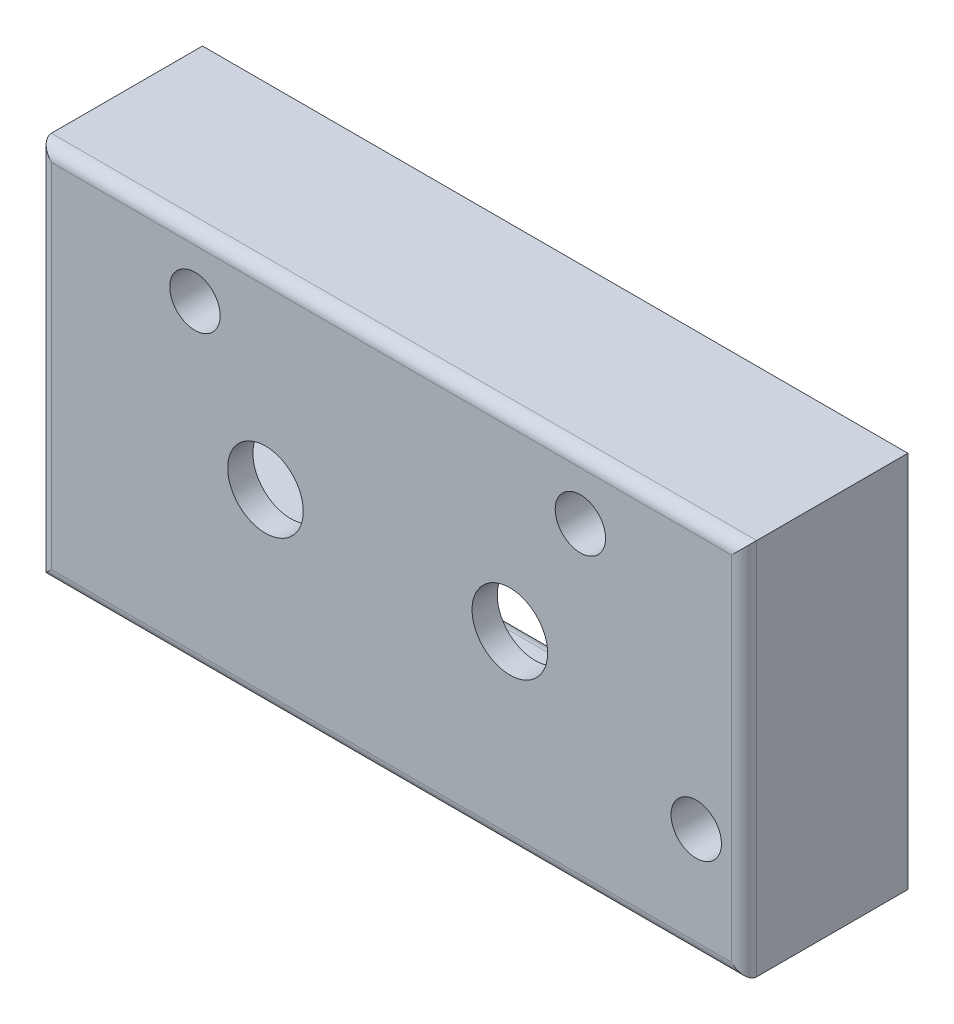
SolidWorks part; units mm, degrees
ref_plane "Plano frontal" through (0, 0, 0) normal (0, 0, 1) x (1, 0, 0)
ref_plane "Plano superior" through (0, 0, 0) normal (0, 1, 0) x (1, 0, 0)
ref_plane "Plano direito" through (0, 0, 0) normal (1, 0, 0) x (0, 0, -1)
sketch "Esboço1" plane through (0, 0, 0) normal (0, 0, 1) x (1, 0, 0)
  line L1 (-14, -7.5) -> (14, -7.5)
  line L2 (-14, -7.5) -> (-14, 7.5)
  line L3 (-14, 7.5) -> (14, 7.5)
  line L4 (14, -7.5) -> (14, 7.5)
  line L5 (-14, -7.5) -> (14, 7.5) construction
  line L6 (-14, 7.5) -> (14, -7.5) construction
  point P0 (0, 0)
  dimension "D1" = 28
  dimension "D2" = 15
extrude "Ressalto-extrusão1" add sketch "Esboço1" along normal blind 6.5
sketch "Esboço2" plane through (0, 0, 0) normal (0, 0, -1) x (-1, 0, 0)
  line L1 (10, 2.75) -> (-10, 2.75)
  line L2 (10, 2.75) -> (10, -2.75)
  line L3 (10, -2.75) -> (-10, -2.75)
  line L4 (-10, 2.75) -> (-10, -2.75)
  line L5 (10, 2.75) -> (-10, -2.75) construction
  line L6 (10, -2.75) -> (-10, 2.75) construction
  point P0 (0, 0)
  dimension "D1" = 5.5
  dimension "D2" = 20
extrude "Corte-extrusão1" cut sketch "Esboço2" against normal blind 5.5
sketch "Esboço3" plane through (0, 0, 0) normal (0, 0, -1) x (-1, 0, 0)
  line L1 (-12.1, -5.125) -> (-12.1, -3.125) construction
  circle A2 centre (-7.5, 5.075) radius 1
  circle A3 centre (7.8, 5.075) radius 1
  circle A5 centre (-12.1, -3.125) radius 1
  dimension "D6" = 2
  dimension "D8" = 2
  dimension "D14" = 2
  dimension "D13" = 2
extrude "Corte-extrusão2" cut sketch "Esboço3" against normal through all
sketch "Esboço4" plane through (0, 0, 0) normal (0, 0, -1) x (-1, 0, 0)
  line L1 (0, -2.75) -> (-5, -2.75)
  line L2 (-10, -2.75) -> (10, -2.75) construction
  line L3 (-5, -2.75) -> (-5, -6)
  line L4 (-5, -6) -> (5, -6)
  line L5 (5, -6) -> (5, -2.75)
  line L6 (5, -2.75) -> (0, -2.75)
  line L7 (14, -7.5) -> (-14, -7.5) construction
  dimension "D1" = 5
  dimension "D2" = 5
  dimension "D3" = 1.5
extrude "Corte-extrusão3" cut sketch "Esboço4" against normal blind 5.5
sketch "Esboço5" plane through (0, 0, 0) normal (0, 0, -1) x (-1, 0, 0)
  line L0 (0, 2.75) -> (-5, 2.75)
  line L1 (10, 2.75) -> (-10, 2.75) construction
  line L2 (-5, 2.75) -> (-5, 6)
  line L3 (-5, 6) -> (5, 6)
  line L4 (5, 6) -> (5, 2.75)
  line L5 (5, 2.75) -> (0, 2.75)
  line L6 (-14, 7.5) -> (14, 7.5) construction
  dimension "D1" = 5
  dimension "D2" = 5
  dimension "D3" = 1.5
extrude "Corte-extrusão4" cut sketch "Esboço5" against normal blind 5.5
sketch "Esboço6" plane through (0, 0, 0) normal (0, 0, -1) x (-1, 0, 0)
  line L1 (10, -2.75) -> (12, -2.75)
  line L2 (10, -2.75) -> (10, 2.75)
  line L3 (10, 2.75) -> (12, 2.75)
  line L4 (12, -2.75) -> (12, 2.75)
  dimension "D1" = 2
extrude "Corte-extrusão5" cut sketch "Esboço6" against normal blind 5.5
sketch "Esboço7" plane through (0, 0, 6.5) normal (0, 0, 1) x (1, 0, 0)
  circle A0 centre (-5, 0) radius 1.5
  circle A1 centre (4.7, -0.025) radius 1.5
  dimension "D2" = 3
  dimension "D4" = 3
extrude "Corte-extrusão6" cut sketch "Esboço7" against normal blind 5.5
fillet "Filete1" radius 0.5 4 edges at (14, 0, 6.5) (0, -7.5, 6.5) (-14, 0, 6.5) (0, 7.5, 6.5)
fillet "Filete2" radius 0.5 12 edges at (5, -4.375, 0) (7.5, -2.75, 0) (10, 0, 0) (7.5, 2.75, 0) (5, 4.375, 0) (0, 6, 0) (0, -6, 0) (-5, -4.375, 0) (-8.5, -2.75, 0) (-12, 0, 0) (-5, 4.375, 0) (-8.5, 2.75, 0)
